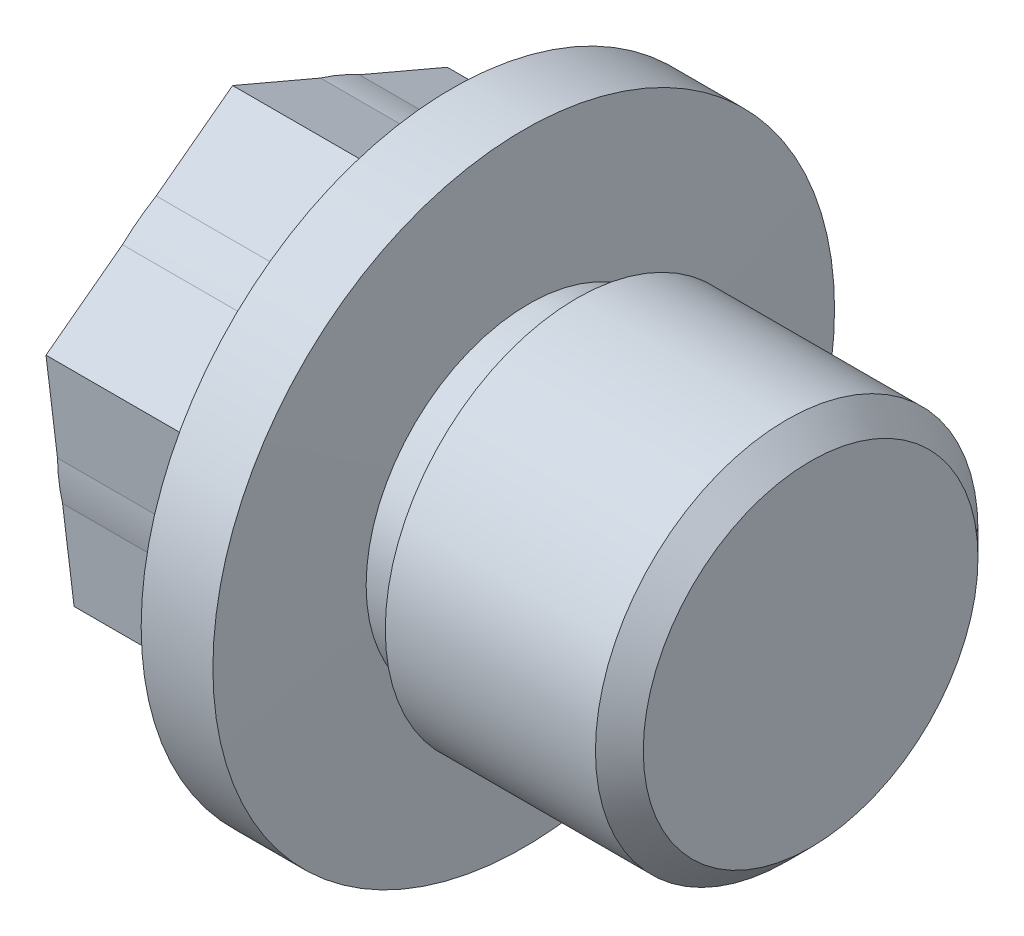
SolidWorks part; units mm, degrees
ref_plane "前视基准面" through (0, 0, 0) normal (0, 0, 1) x (1, 0, 0)
ref_plane "上视基准面" through (0, 0, 0) normal (0, 1, 0) x (1, 0, 0)
ref_plane "右视基准面" through (0, 0, 0) normal (1, 0, 0) x (0, 0, -1)
other "Configuration Table"
sketch "草图1" plane through (0, 0, 0) normal (0, 0, 1) x (1, 0, 0)
  line L0 (0, 0) -> (46.2635, 0) construction
  line L1 (0, 0) -> (0, 8.5)
  line L2 (0, 8.5) -> (8, 8.5)
  line L3 (8, 8.5) -> (8, 13)
  line L4 (8, 13) -> (11, 13)
  line L5 (11, 13) -> (11.2093, 6.8)
  line L6 (11.2093, 6.8) -> (13.2093, 6.8)
  line L7 (13.2093, 6.8) -> (13.2093, 8)
  line L8 (13.2093, 8) -> (23, 8)
  line L9 (23, 8) -> (23, 0)
  line L10 (0, 0) -> (23, 0)
  dimension "D1" = 8.5
  dimension "D2" = 8
  dimension "D3" = 4.5
  dimension "D4" = 3
  dimension "D5" = 8
  dimension "D6" = 2
  dimension "D7" = 1.2
  dimension "D8" = 23
revolve "旋转1" add sketch "草图1" angle 360 about L0
sketch "草图2" plane through (0, 0, 0) normal (-1, 0, 0) x (0, 0, 1)
  line L1 (7.8052, -5.8629) -> (8.98, 3.8281)
  line L2 (8.98, 3.8281) -> (1.1748, 9.691)
  line L3 (1.1748, 9.691) -> (-7.8052, 5.8629)
  line L4 (-7.8052, 5.8629) -> (-8.98, -3.8281)
  line L5 (-8.98, -3.8281) -> (-1.1748, -9.691)
  line L6 (-1.1748, -9.691) -> (7.8052, -5.8629)
  circle A0 centre (0, 0) radius 8.5 construction
  circle A1 centre (0, 0) radius 8.5
  circle A2 centre (0, 0) radius 8.4541 construction
  circle M1 centre (0, 0) radius 8.5
extrude "凸台-拉伸1" add sketch "草图2" against normal up to surface (8 mm away) contours L6 L1 L2 L3 L4 L5 M1 | L3 L4 M1 | L2 L3 M1 | L1 L2 M1 | L6 L1 M1 | L5 L6 M1 | L4 L5 M1 up to face at (8, 0, 8.5)
chamfer "倒角1" distance 1 angle 45 1 edges at (23, 0, 8)
thread "螺纹线1" [suppressed] pitch 0.3175 start angle 0, offset 0, length 10, pitch 0.3175, diameter 17
ref_plane "基准面1" through (13.2093, 0, -8.5) normal (0, -1, 0) x (0, 0, -1)
sketch "螺纹线轮廓1" plane through (13.2093, 0, -8.5) normal (0, -1, 0) x (0, 0, -1)
  line L0 (0, 0) -> (0, 0.3175) construction
  line L11 (0, 0) -> (0, 0.2778)
  line L12 (0, 0.2778) -> (-0.1719, 0.1786)
  line L13 (-0.1719, 0.1786) -> (-0.1719, 0.0992)
  line L15 (-0.1719, 0.0992) -> (0, 0)
  line L17 (-0.1719, 0.1389) -> (0, 0.1389) construction
  point P2 (0, 0)
  dimension "Pitch" = 0.3175
  dimension "Profile_Angle" = 60
  dimension "Profile_Land" = 0.0794
  dimension "Profile_Height" = 0.1719
